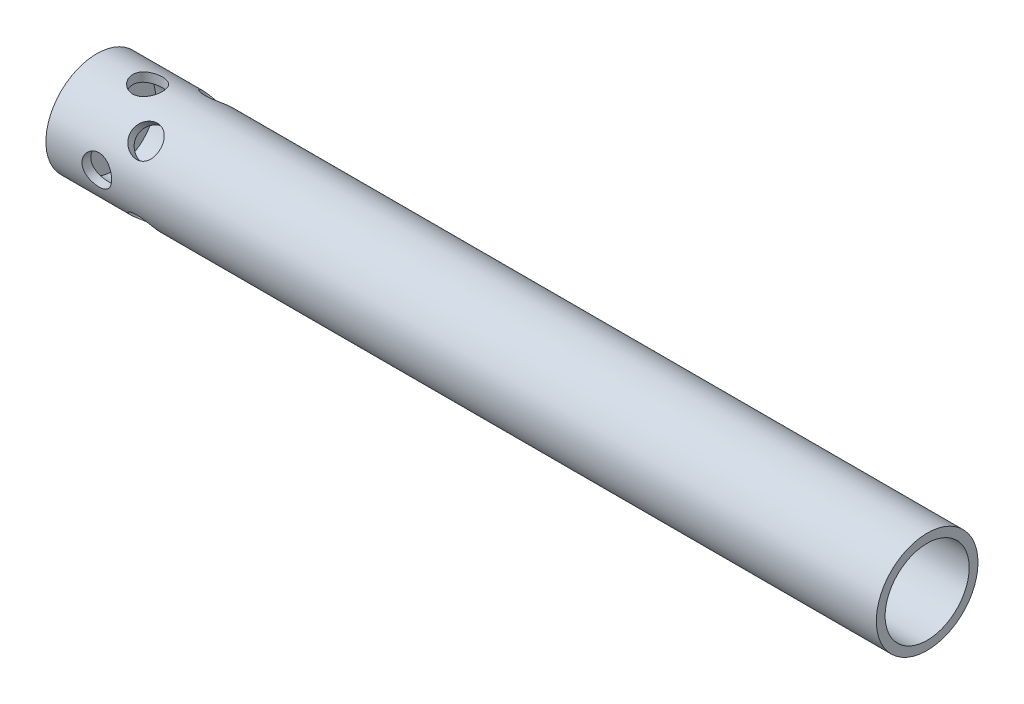
SolidWorks part; units mm, degrees
material "6061-T6 (SS)"
ref_plane "Front" through (0, 0, 0) normal (0, 0, 1) x (1, 0, 0)
ref_plane "Top" through (0, 0, 0) normal (0, 1, 0) x (1, 0, 0)
ref_plane "Right" through (0, 0, 0) normal (1, 0, 0) x (0, 0, -1)
sketch "Sketch1" plane through (0, 0, 0) normal (1, 0, 0) x (0, 0, -1)
  circle A0 centre (0, 0) radius 9.525
  circle A1 centre (0, 0) radius 7.874
  dimension "D1" = 19.05
  dimension "D2" = 1.651
extrude "Boss-Extrude1" add sketch "Sketch1" along normal blind 152.4
sketch "Sketch2" plane through (0, 0, 0) normal (1, 0, 0) x (0, 0, -1)
  circle A0 centre (0, 0) radius 9.525
extrude "Boss-Extrude2" add sketch "Sketch2" against normal blind 3.175
sketch "Sketch3" plane through (0, 0, 0) normal (0, 0, 1) x (1, 0, 0)
  line L0 (0, 0) -> (71.7681, 0) construction
  line L1 (-35.8841, 0) -> (35.8841, 0) construction
  circle A0 centre (6.35, 0) radius 2.7781
  dimension "D1" = 5.5562
  dimension "D2" = 6.35
extrude "Cut-Extrude1" cut sketch "Sketch3" against normal mid plane 25.4
pattern_circular "CirPattern1" count 2 every 90 about axis through (152.4, 0, 0) along (-1, 0, 0) of "Cut-Extrude1"
ref_plane "Plane1" through (0, 0, 0) normal (0, -0.7071, 0.7071) x (1, 0, 0)
sketch "Sketch4" plane through (0, 0, 0) normal (0, -0.7071, 0.7071) x (1, 0, 0)
  line L0 (-35.8841, 0) -> (35.8841, 0) construction
  line L1 (0, 0) -> (71.7681, 0) construction
  circle A0 centre (12.7, 0) radius 2.7781
  dimension "D1" = 12.7
extrude "Cut-Extrude2" cut sketch "Sketch4" against normal mid plane 25.4 contours A0
pattern_circular "CirPattern2" count 2 every 90 about axis through (152.4, 0, 0) along (-1, 0, 0) of "Cut-Extrude2"
